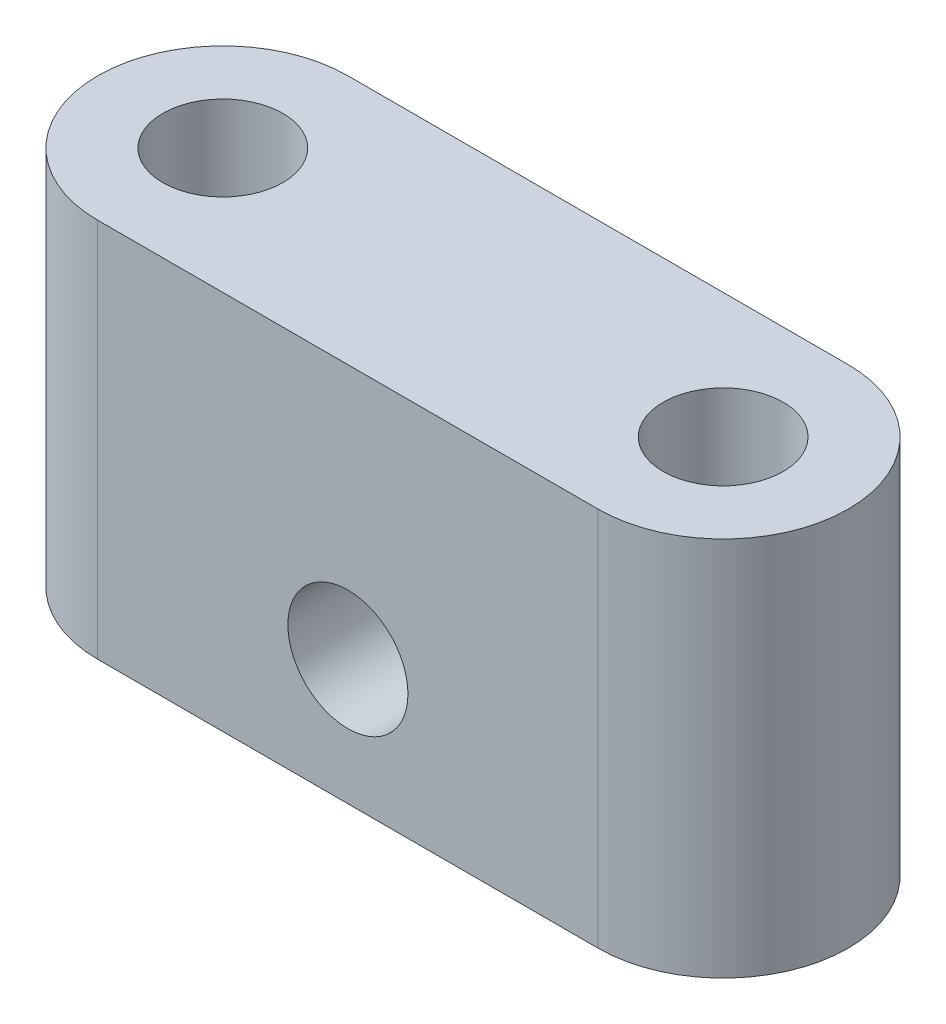
SolidWorks part; units mm, degrees
ref_plane "Front Plane" through (0, 0, 0) normal (0, 0, 1) x (1, 0, 0)
ref_plane "Top Plane" through (0, 0, 0) normal (0, 1, 0) x (1, 0, 0)
ref_plane "Right Plane" through (0, 0, 0) normal (1, 0, 0) x (0, 0, -1)
sketch "Sketch1" plane through (0, 0, 0) normal (0, 1, 0) x (1, 0, 0)
  line L0 (-25, 0) -> (25, 0) construction
  line L1 (-25, 12.5) -> (25, 12.5)
  line L2 (-25, -12.5) -> (25, -12.5)
  arc A0 (-25, 12.5) -> (-25, -12.5) centre (-25, 0) ccw
  arc A1 (25, -12.5) -> (25, 12.5) centre (25, 0) ccw
  circle A2 centre (-25, 0) radius 6
  circle A3 centre (25, 0) radius 6
  point P2 (0, 0)
  dimension "D1" = 12.5
  dimension "D3" = 12
  dimension "D2" = 50
extrude "Boss-Extrude1" add sketch "Sketch1" along normal mid plane 38
hole_wizard "Hole1" positions "Sketch2" profile "Sketch3" legacy
sketch "Sketch2" plane through (0, 0, 12.5) normal (0, 0, 1) x (1, 0, 0)
  line L1 (-25, -19) -> (25, -19) construction
  point P0 (0, -6.5)
  dimension "D1" = 12.5
sketch "Sketch3" plane through (0, -6.5, 12.5) normal (1, 0, 0) x (0, -1, 0)
  line L0 (0, 0) -> (0, 12.5)
  line L1 (0, 12.5) -> (6, 12.5)
  line L2 (6, 12.5) -> (6, 0)
  line L3 (6, 0) -> (0, 0)
  line L4 (0, 110) -> (0, -10) construction
  dimension "Diameter" = 12
  dimension "Depth" = 12.5
